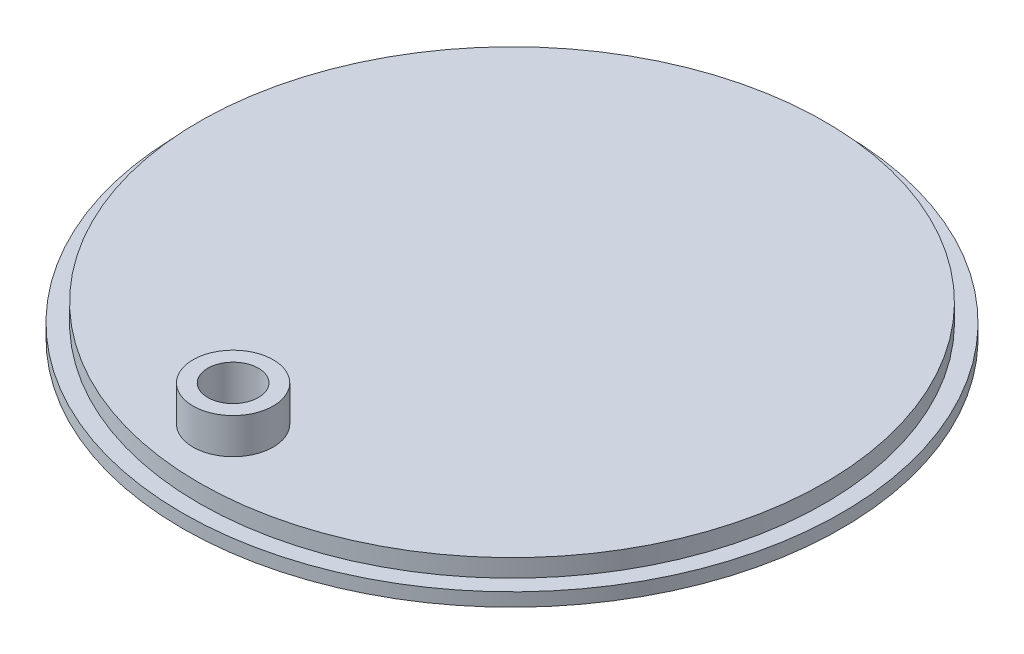
SolidWorks part; units mm, degrees
ref_plane "Front Plane" through (0, 0, 0) normal (0, 0, 1) x (1, 0, 0)
ref_plane "Top Plane" through (0, 0, 0) normal (0, 1, 0) x (1, 0, 0)
ref_plane "Right Plane" through (0, 0, 0) normal (1, 0, 0) x (0, 0, -1)
sketch "Sketch1" plane through (0, 0, 0) normal (0, 1, 0) x (1, 0, 0)
  circle A0 centre (0, 0) radius 70.25
  dimension "D1" = 140.5
extrude "Boss-Extrude1" add sketch "Sketch1" along normal blind 4
sketch "Sketch2" plane through (0, 4, 0) normal (0, 1, 0) x (1, 0, 0)
  circle A0 centre (-7.625, -55) radius 9
  dimension "D1" = 18
  dimension "D2" = 55
sketch "Sketch3" plane through (0, 0, 0) normal (0, -1, 0) x (1, 0, 0)
  circle A0 centre (0, 0) radius 74
  dimension "D1" = 148
extrude "Boss-Extrude2" add sketch "Sketch3" along normal blind 3
extrude "Boss-Extrude3" add sketch "Sketch2" along normal blind 8
sketch "Sketch4" plane through (0, 12, 0) normal (0, 1, 0) x (1, 0, 0)
  circle A0 centre (-7.625, -55) radius 5.7
  dimension "D1" = 11.4
sketch "Sketch6" plane through (0, -3, 0) normal (0, -1, 0) x (1, 0, 0)
  circle A0 centre (-7.625, 55) radius 7
  dimension "D1" = 14
extrude "Cut-Extrude2" cut sketch "Sketch6" against normal blind 3.5
extrude "Cut-Extrude3" cut sketch "Sketch4" against normal through all
